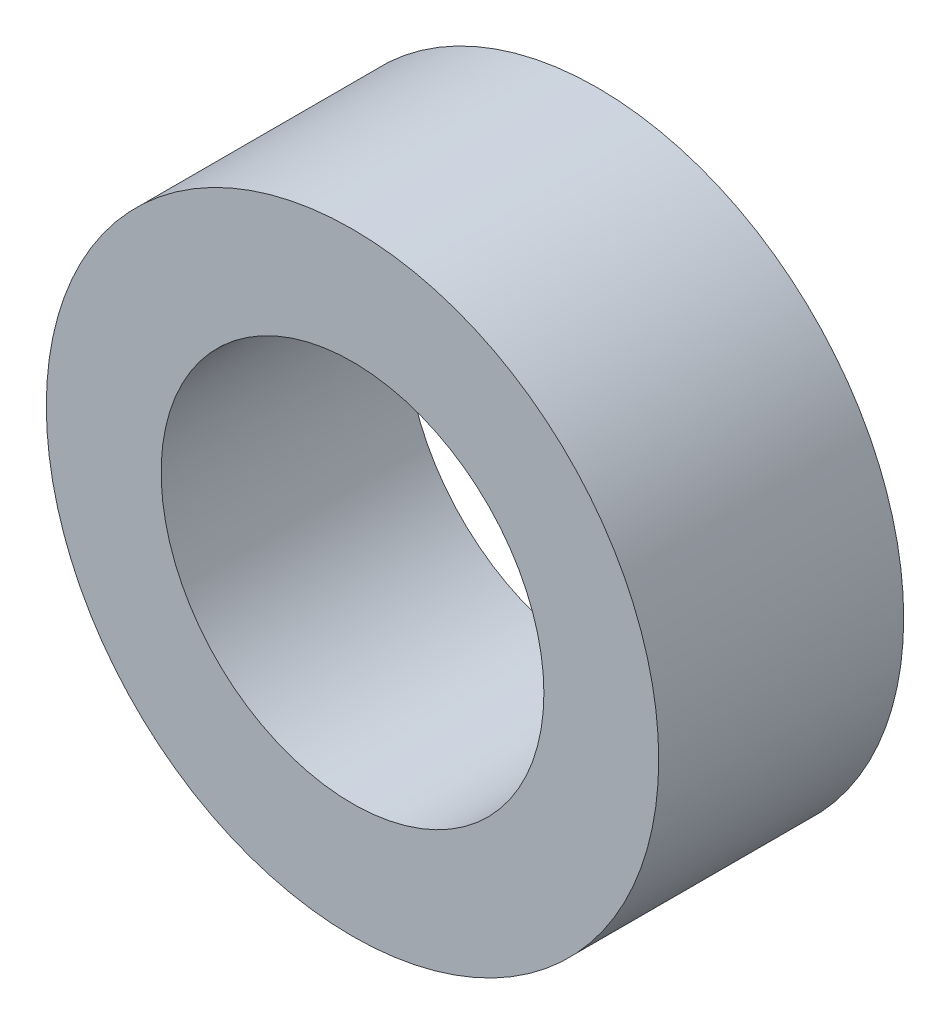
SolidWorks part; units mm, degrees
material "尼龙 101"
ref_plane "前视基准面" through (0, 0, 0) normal (0, 0, 1) x (1, 0, 0)
ref_plane "上视基准面" through (0, 0, 0) normal (0, 1, 0) x (1, 0, 0)
ref_plane "右视基准面" through (0, 0, 0) normal (1, 0, 0) x (0, 0, -1)
sketch "草图1" plane through (0, 0, 0) normal (0, 0, 1) x (1, 0, 0)
  circle A0 centre (0, 0) radius 2.5
  circle A1 centre (0, 0) radius 4
  dimension "D1" = 5
  dimension "D2" = 8
extrude "凸台-拉伸1" add sketch "草图1" along normal blind 3.2
